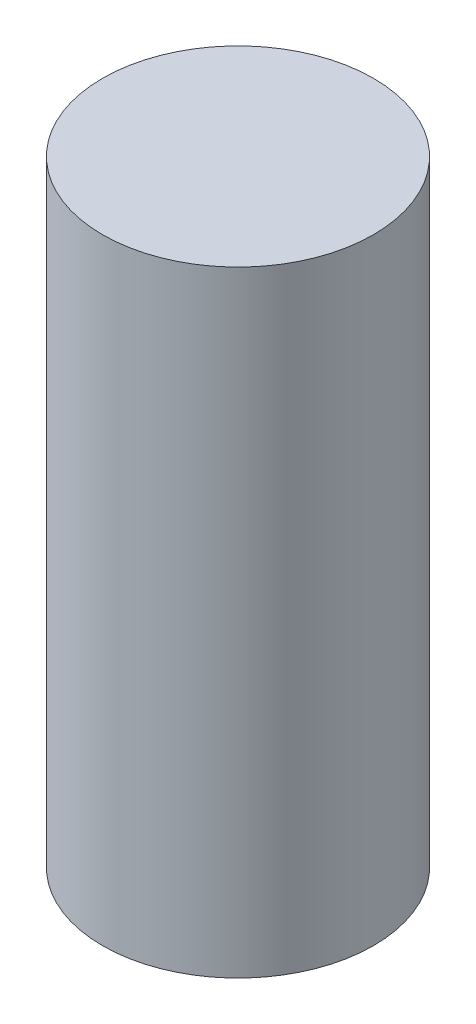
SolidWorks part; units mm, degrees
ref_plane "Front Plane" through (0, 0, 0) normal (0, 0, 1) x (1, 0, 0)
ref_plane "Top Plane" through (0, 0, 0) normal (0, 1, 0) x (1, 0, 0)
ref_plane "Right Plane" through (0, 0, 0) normal (1, 0, 0) x (0, 0, -1)
sketch "Sketch2" plane through (0, 0, 0) normal (0, 1, 0) x (1, 0, 0)
  circle A0 centre (0, 0) radius 11
  dimension "D1" = 22
extrude "Boss-Extrude1" add sketch "Sketch2" along normal blind 50
